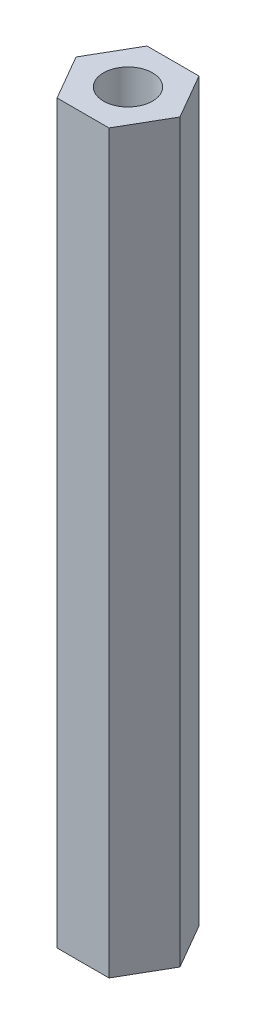
SolidWorks part; units mm, degrees
ref_plane "Front Plane" through (0, 0, 0) normal (0, 0, 1) x (1, 0, 0)
ref_plane "Top Plane" through (0, 0, 0) normal (0, 1, 0) x (1, 0, 0)
ref_plane "Right Plane" through (0, 0, 0) normal (1, 0, 0) x (0, 0, -1)
sketch "Sketch1" plane through (0, 0, 0) normal (0, 1, 0) x (1, 0, 0)
  line L1 (3.1754, 0) -> (1.5877, 2.75)
  line L2 (1.5877, 2.75) -> (-1.5877, 2.75)
  line L3 (-1.5877, 2.75) -> (-3.1754, 0)
  line L4 (-3.1754, 0) -> (-1.5877, -2.75)
  line L5 (-1.5877, -2.75) -> (1.5877, -2.75)
  line L6 (1.5877, -2.75) -> (3.1754, 0)
  circle A0 centre (0, 0) radius 2.75 construction
  dimension "D1" = 5.5
extrude "Boss-Extrude1" add sketch "Sketch1" along normal blind 45
sketch "Sketch2" plane through (0, 45, 0) normal (0, 1, 0) x (1, 0, 0)
  circle A0 centre (0, 0) radius 1.5
  dimension "D1" = 3
extrude "Cut-Extrude1" cut sketch "Sketch2" against normal blind 10
ref_plane "Plane1" through (0, 22.5, 0) normal (0, -1, 0) x (-1, 0, 0)
mirror "Mirror1" about plane through (0, 22.5, 0) normal (0, -1, 0) of "Cut-Extrude1"
